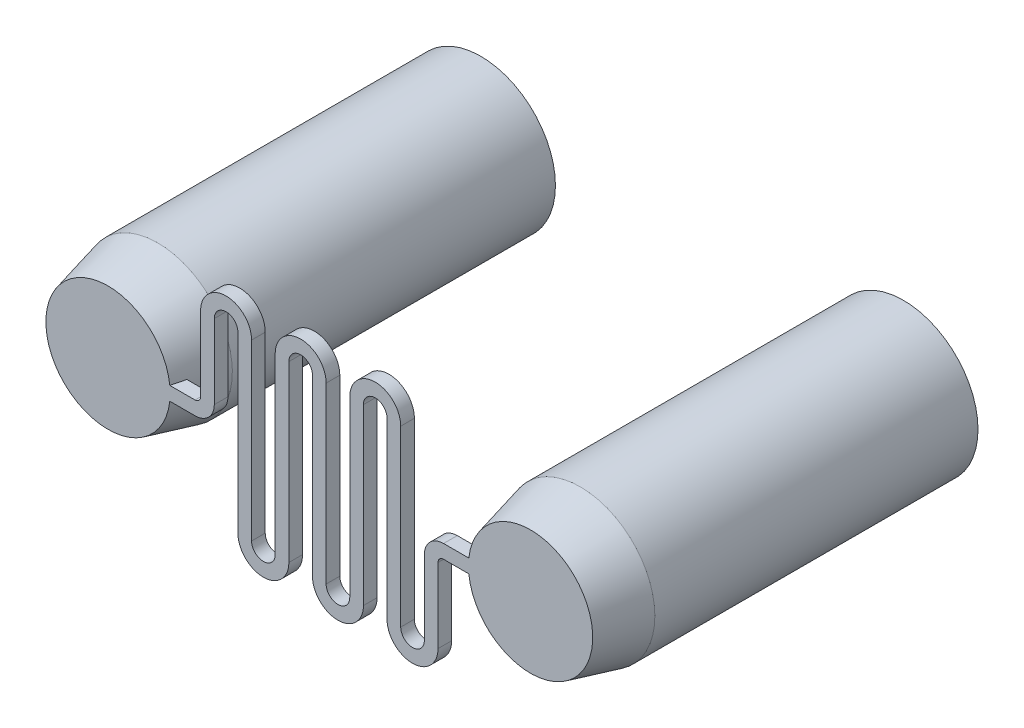
SolidWorks part; units mm, degrees
ref_plane "Front Plane" through (0, 0, 0) normal (0, 0, 1) x (1, 0, 0)
ref_plane "Top Plane" through (0, 0, 0) normal (0, 1, 0) x (1, 0, 0)
ref_plane "Right Plane" through (0, 0, 0) normal (1, 0, 0) x (0, 0, -1)
sketch "Sketch2" plane through (0, 0, 0) normal (0, 0, 1) x (1, 0, 0)
  line L3 (-20.5, -0.55) -> (-13.5, -0.55)
  line L6 (-11.95, 1) -> (-11.95, 7)
  line L9 (-10.05, 7) -> (-10.05, 0)
  line L12 (-10.05, 0) -> (-10.05, -7)
  line L15 (-5.95, -7) -> (-5.95, 0)
  line L18 (-5.95, 0) -> (-5.95, 7)
  line L21 (-4.05, 7) -> (-4.05, 0)
  line L22 (-4.05, 0) -> (-4.05, -7)
  line L23 (0.05, -7) -> (0.05, 0)
  line L24 (0.05, 0) -> (0.05, 7)
  line L25 (1.95, 7) -> (1.95, 0)
  line L26 (1.95, 0) -> (1.95, -7)
  line L27 (6.05, -7) -> (6.05, -1)
  line L28 (6.5, -0.55) -> (13.5, -0.55)
  line L29 (-20.5, 0.55) -> (-13.5, 0.55)
  line L30 (-13.05, 1) -> (-13.05, 7)
  line L31 (-8.95, 7) -> (-8.95, 0)
  line L32 (-8.95, 0) -> (-8.95, -7)
  line L33 (-7.05, -7) -> (-7.05, 0)
  line L34 (-7.05, 0) -> (-7.05, 7)
  line L35 (-2.95, 7) -> (-2.95, 0)
  line L36 (-2.95, 0) -> (-2.95, -7)
  line L37 (-1.05, -7) -> (-1.05, 0)
  line L38 (-1.05, 0) -> (-1.05, 7)
  line L39 (3.05, 7) -> (3.05, 0)
  line L40 (3.05, 0) -> (3.05, -7)
  line L41 (4.95, -7) -> (4.95, -1)
  line L42 (6.5, 0.55) -> (13.5, 0.55)
  arc A0 (13.5, -0.55) -> (13.5, 0.55) centre (13.5, 0) ccw
  arc A8 (-11.95, 1) -> (-13.5, -0.55) centre (-13.5, 1) cw
  arc A9 (-11.95, 7) -> (-10.05, 7) centre (-11, 7) cw
  arc A10 (-10.05, -7) -> (-5.95, -7) centre (-8, -7) ccw
  arc A11 (-5.95, 7) -> (-4.05, 7) centre (-5, 7) cw
  arc A12 (-4.05, -7) -> (0.05, -7) centre (-2, -7) ccw
  arc A13 (0.05, 7) -> (1.95, 7) centre (1, 7) cw
  arc A14 (1.95, -7) -> (6.05, -7) centre (4, -7) ccw
  arc A15 (6.05, -1) -> (6.5, -0.55) centre (6.5, -1) cw
  arc A16 (-13.05, 1) -> (-13.5, 0.55) centre (-13.5, 1) cw
  arc A17 (-13.05, 7) -> (-8.95, 7) centre (-11, 7) cw
  arc A18 (-8.95, -7) -> (-7.05, -7) centre (-8, -7) ccw
  arc A19 (-7.05, 7) -> (-2.95, 7) centre (-5, 7) cw
  arc A20 (-2.95, -7) -> (-1.05, -7) centre (-2, -7) ccw
  arc A21 (-1.05, 7) -> (3.05, 7) centre (1, 7) cw
  arc A22 (3.05, -7) -> (4.95, -7) centre (4, -7) ccw
  arc A23 (4.95, -1) -> (6.5, 0.55) centre (6.5, -1) cw
  arc A24 (-20.5, 0.55) -> (-20.5, -0.55) centre (-20.5, 0) ccw
  point P4 (0, 0)
  point P32 (5.5, 0)
  point P35 (-12.5, 0)
  dimension "D1" = 8
extrude "Boss-Extrude1" add sketch "Sketch2" along normal blind 1.1
ref_plane "Plane1" through (0, 0, 0) normal (0, -1, 0) x (-1, 0, 0)
sketch "Sketch3" plane through (0, 0, 0) normal (0, -1, 0) x (-1, 0, 0)
  line L0 (20.5, -1.1) -> (25.5, -1.1)
  line L2 (20.5, -1.1) -> (20.5, 28.9)
  line L3 (20.5, 28.9) -> (26.5, 28.9)
  line L4 (26.5, 28.9) -> (26.5, 2.9)
  line L5 (26.5, 2.9) -> (25.5, -1.1)
  dimension "D1" = 30
  dimension "D2" = 5
  dimension "D4" = 6
revolve "Revolve1" add sketch "Sketch3" angle 360 about L2
ref_plane "Plane2" through (0, 0, 0) normal (0, -1, 0) x (-1, 0, 0)
sketch "Sketch4" plane through (0, 0, 0) normal (0, -1, 0) x (-1, 0, 0)
  line L0 (-13.5, -1.1) -> (-18.5, -1.1)
  line L2 (-13.5, -1.1) -> (-13.5, 28.9)
  line L3 (-13.5, 28.9) -> (-19.5, 28.9)
  line L4 (-19.5, 28.9) -> (-19.5, 2.9)
  line L5 (-19.5, 2.9) -> (-18.5, -1.1)
  dimension "D1" = 6
  dimension "D2" = 30
  dimension "D4" = 5
revolve "Revolve2" add sketch "Sketch4" angle 360 about L2
sketch "Sketch5" plane through (0, 0, -28.9) normal (0, 0, -1) x (-1, 0, 0)
  circle A0 centre (-13.5, 0) radius 5
  circle A1 centre (20.5, 0) radius 5
  dimension "D1" = 10
  dimension "D2" = 10
extrude "Cut-Extrude1" cut sketch "Sketch5" against normal blind 28
